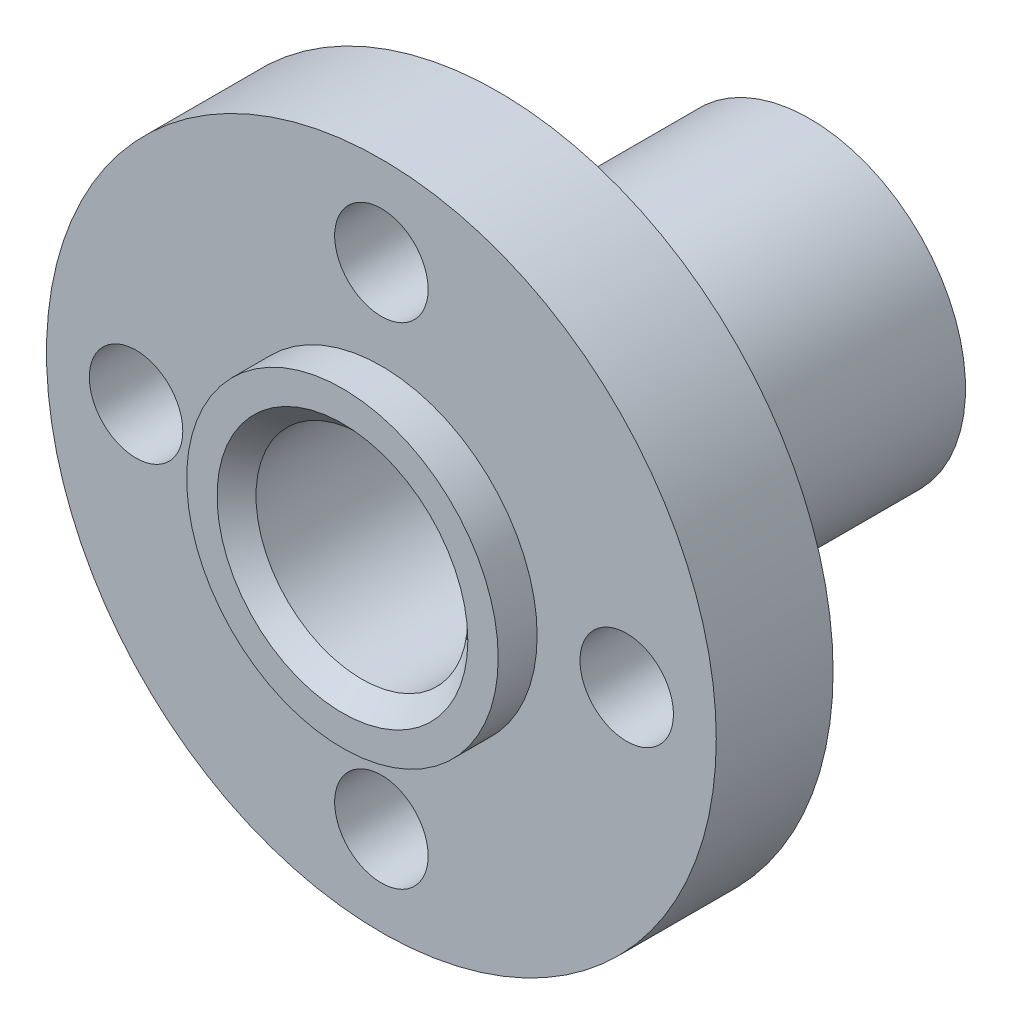
SolidWorks part; units mm, degrees
ref_plane "Front Plane" through (0, 0, 0) normal (0, 0, 1) x (1, 0, 0)
ref_plane "Top Plane" through (0, 0, 0) normal (0, 1, 0) x (1, 0, 0)
ref_plane "Right Plane" through (0, 0, 0) normal (1, 0, 0) x (0, 0, -1)
sketch "Sketch3" plane through (0, 0, 0) normal (0, 0, 1) x (1, 0, 0)
  circle A0 centre (0, 0) radius 10.75
  dimension "D1" = 21.5
extrude "Boss-Extrude1" add sketch "Sketch3" against normal blind 3.75
sketch "Sketch4" plane through (0, 0, -3.75) normal (0, 0, -1) x (-1, 0, 0)
  circle A0 centre (0, 0) radius 5
  dimension "D1" = 10
extrude "Boss-Extrude2" add sketch "Sketch4" along normal blind 10
sketch "Sketch5" plane through (0, 0, 0) normal (0, 0, 1) x (1, 0, 0)
  circle A0 centre (0, 0) radius 5 construction
  circle A1 centre (0, 0) radius 5
extrude "Boss-Extrude3" add sketch "Sketch5" along normal blind 1.25
hole_wizard "M8 Tapped Hole1" positions "Sketch7" profile "Sketch8" tap size "M8" standard "ISO"
sketch "Sketch7" plane through (0, 0, 1.25) normal (0, 0, 1) x (1, 0, 0)
  point P0 (0, 0)
sketch "Sketch8" plane through (0, 0, 1.25) normal (1, 0, 0) x (0, -1, 0)
  line L0 (0, 0) -> (0, 17.0429)
  line L1 (0, 17.0429) -> (3.4, 15)
  line L2 (3.4, 15) -> (3.4, 0.625)
  line L3 (3.4, 0.625) -> (4.025, 0)
  line L5 (4.025, 0) -> (0, 0)
  line L6 (-3.4, 0.625) -> (-4.025, 0) construction
  line L10 (0, 17.0429) -> (-3.4, 15) construction
  line L11 (0, -6.35) -> (0, 107.95) construction
  dimension "Tap Drill Dia." = 6.8
  dimension "Tap Drill Depth" = 15
  dimension "Near C'Sink Dia." = 8.05
  dimension "Near C'Sink Angle" = 90
  dimension "Drill Angle" = 118
cosmetic thread "Hole Thread2" parameters "D1"=16, "D2"=8
sketch "Sketch9" plane through (0, 0, 0) normal (0, 0, 1) x (1, 0, 0)
  line L0 (-5, 0) -> (-10.75, 0) construction
  circle A0 centre (-7.875, 0) radius 1.5
  circle A4 centre (0, 0) radius 10.75 construction
  circle A5 centre (0, 0) radius 5 construction
  circle A6 centre (0, 7.875) radius 1.5
  circle A7 centre (7.875, 0) radius 1.5
  circle A8 centre (0, -7.875) radius 1.5
  point P5 (-5, 0)
  point P20 (0, 0)
  dimension "D1" = 3
  dimension "D2" = 4
extrude "Cut-Extrude1" cut sketch "Sketch9" against normal up to surface (3.75 mm away) up to face at (-5, 0, -3.75)
